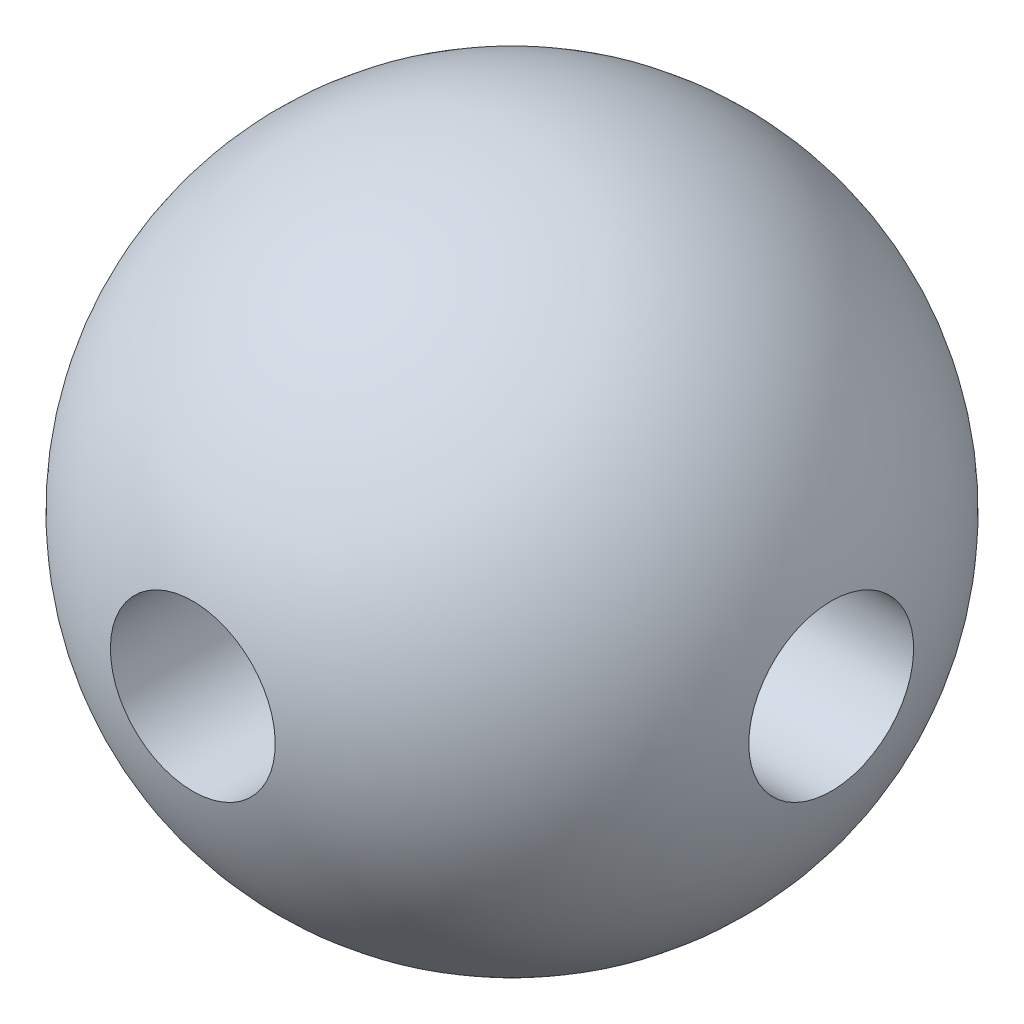
SolidWorks part; units mm, degrees
ref_plane "Front Plane" through (0, 0, 0) normal (0, 0, 1) x (1, 0, 0)
ref_plane "Top Plane" through (0, 0, 0) normal (0, 1, 0) x (1, 0, 0)
ref_plane "Right Plane" through (0, 0, 0) normal (1, 0, 0) x (0, 0, -1)
sketch "Sketch1" plane through (0, 0, 0) normal (0, 0, 1) x (1, 0, 0)
  line L0 (0, 3) -> (0, -3)
  circle A0 centre (0, 0) radius 3
  dimension "D1" = 6
revolve "Revolve1" add sketch "Sketch1" angle 360 about L0
sketch "Sketch2" plane through (0, 0, 0) normal (1, 0, 0) x (0, 0, -1)
  circle A0 centre (0, 0) radius 0.75
  dimension "D1" = 1.5
extrude "Cut-Extrude1" cut sketch "Sketch2" against normal through all both and the other way through all
sketch "Sketch3" plane through (0, 0, 0) normal (0, 0, 1) x (1, 0, 0)
  circle A0 centre (0, 0) radius 0.75
  dimension "D1" = 1.5
extrude "Cut-Extrude2" cut sketch "Sketch3" against normal through all both and the other way through all
